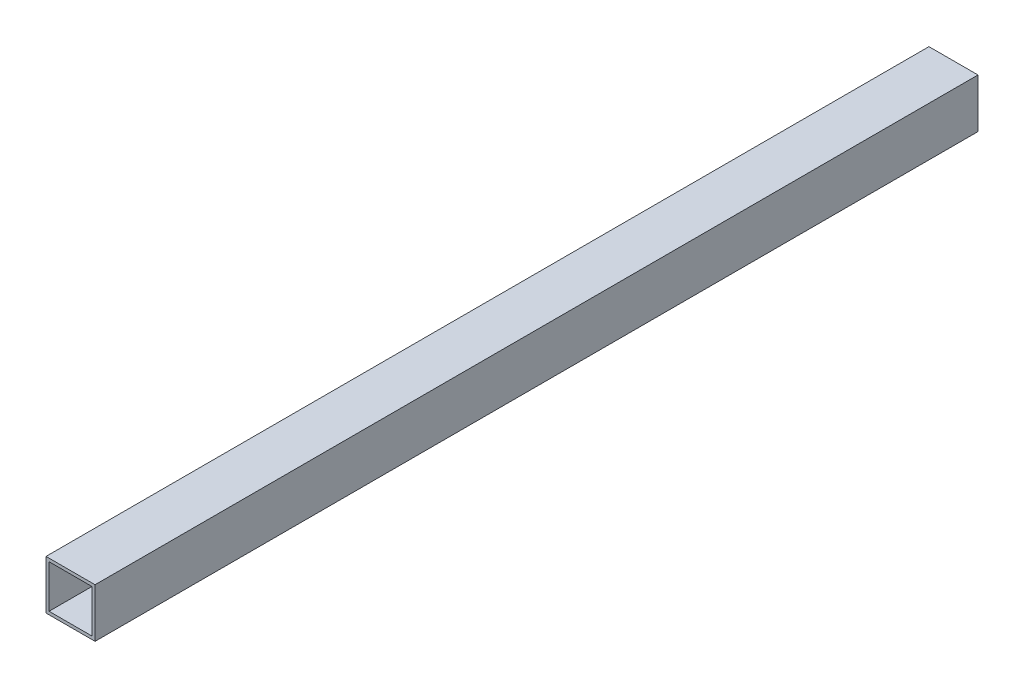
SolidWorks part; units mm, degrees
ref_plane "Front Plane" through (0, 0, 0) normal (0, 0, 1) x (1, 0, 0)
ref_plane "Top Plane" through (0, 0, 0) normal (0, 1, 0) x (1, 0, 0)
ref_plane "Right Plane" through (0, 0, 0) normal (1, 0, 0) x (0, 0, -1)
sketch "Sketch1" plane through (0, 0, 0) normal (0, 0, 1) x (1, 0, 0)
  line L1 (12.7, -12.7) -> (-12.7, -12.7)
  line L2 (12.7, -12.7) -> (12.7, 12.7)
  line L3 (12.7, 12.7) -> (-12.7, 12.7)
  line L4 (-12.7, -12.7) -> (-12.7, 12.7)
  line L5 (12.7, -12.7) -> (-12.7, 12.7) construction
  line L6 (12.7, 12.7) -> (-12.7, -12.7) construction
  point P0 (0, 0)
  dimension "D1" = 25.4
extrude "Extrude-Thin1" add sketch "Sketch1" along normal blind 457.2 thin
